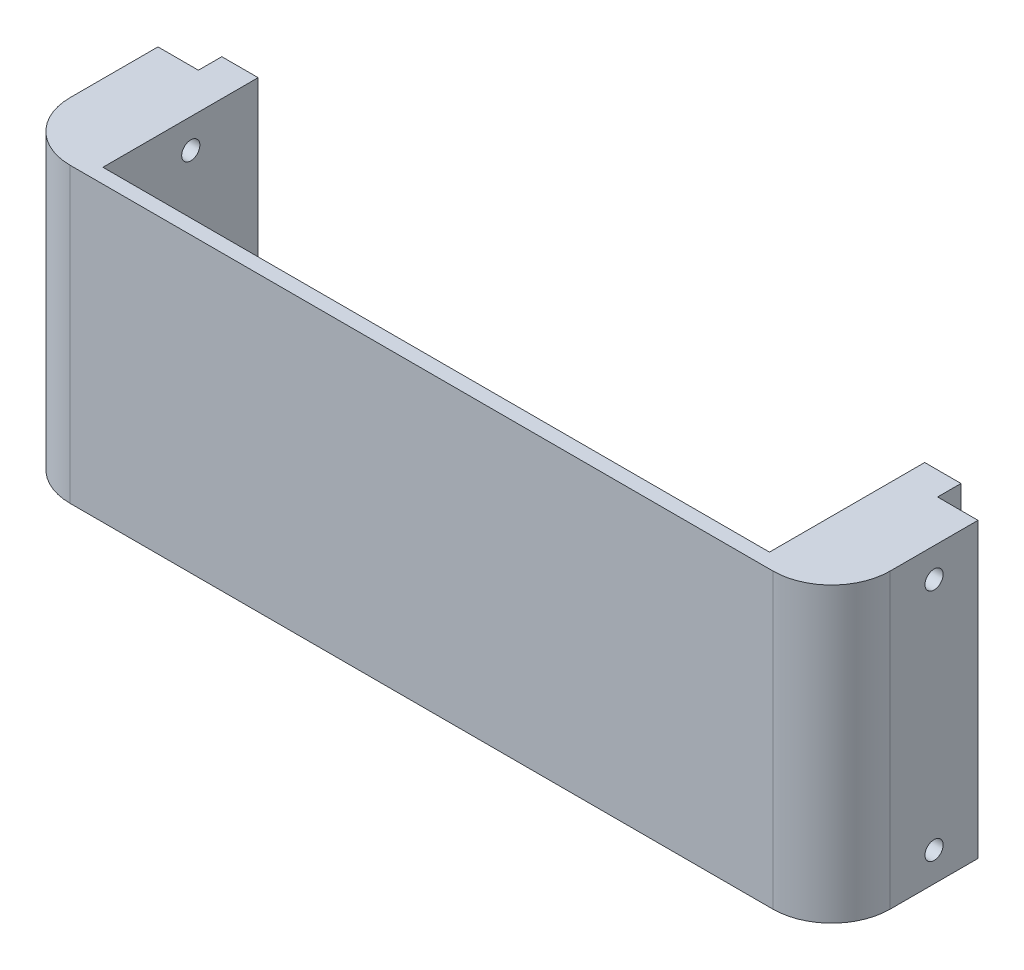
SolidWorks part; units mm, degrees
ref_plane "Front Plane" through (0, 0, 0) normal (0, 0, 1) x (1, 0, 0)
ref_plane "Top Plane" through (0, 0, 0) normal (0, 1, 0) x (1, 0, 0)
ref_plane "Right Plane" through (0, 0, 0) normal (1, 0, 0) x (0, 0, -1)
other "Configuration Table"
sketch "草图1" plane through (0, 0, 0) normal (0, 0, 1) x (1, 0, 0)
  line L0 (-15, 22) -> (-15, -22)
  line L1 (0, 22) -> (15, 22)
  line L2 (0, 22) -> (-15, 22)
  line L3 (15, 22) -> (15, -22)
  line L4 (15, -22) -> (-15, -22)
extrude "凸台-拉伸1" add sketch "草图1" along normal blind 14 contours L0 L4 L3 L1 L2
sketch "草图2" plane through (0, 22, 0) normal (0, 1, 0) x (1, 0, 0)
  line L3 (10, -4) -> (15, -14)
  line L4 (15, -14) -> (-15, -14)
  line L6 (-15, -14) -> (-10, -4)
  line L8 (3.1, -4) -> (3.1, 0)
  line L9 (-15, 0) -> (15, 0) construction
  line L10 (3.1, 0) -> (15, 0)
  line L11 (15, 0) -> (15, -14)
  line L12 (10, -4) -> (3.1, -4)
  line L13 (-3.1, -4) -> (-10, -4)
  line L14 (-15, -14) -> (-15, 0)
  line L15 (-15, 0) -> (-3.1, 0)
  line L16 (-3.1, 0) -> (-3.1, -4)
  line M14 (15, 0) -> (-15, 0)
  line M15 (-15, 0) -> (-15, -14)
  line M17 (15, -14) -> (15, 0)
extrude "切除-拉伸1" cut sketch "草图2" against normal blind 44 contours L16 L6 L13 M14 M15 | L12 L3 L8 M17 M14
sketch "草图3" plane through (0, 0, 0) normal (0, 0, -1) x (-1, 0, 0)
  line L2 (-3.1, 3.1) -> (-3.1, -3.1)
  line L4 (3.1, -22) -> (3.1, 22) construction
  line L5 (3.1, 3.1) -> (-3.1, 3.1)
  line L6 (-3.1, -22) -> (-3.1, 22) construction
  line L9 (-3.1, -3.1) -> (3.1, -3.1)
  line L10 (3.1, -22) -> (3.1, 22) construction
  line L11 (3.1, -3.1) -> (3.1, 3.1)
extrude "切除-拉伸2" cut sketch "草图3" against normal blind 4 contours L2 L9 L11 L5
sketch "草图4" plane through (0, 0, 14) normal (0, 0, 1) x (1, 0, 0)
  circle A0 centre (0, 0) radius 4
extrude "切除-拉伸3" cut sketch "草图4" against normal blind 5
sketch "草图5" plane through (0, 0, 9) normal (0, 0, 1) x (1, 0, 0)
  circle A0 centre (0, 0) radius 2.6
extrude "切除-拉伸4" cut sketch "草图5" against normal blind 5 contours A0
sketch "草图6" plane through (0, 0, 14) normal (0, 0, 1) x (1, 0, 0)
  circle A0 centre (0, 0) radius 4
extrude "凸台-拉伸2" add sketch "草图6" against normal blind 10
sketch "草图7" plane through (0, -22, 0) normal (0, -1, 0) x (-1, 0, 0)
  line L0 (-10, -4) -> (-3.1, -4) construction
  line L1 (3.1, 0) -> (-3.1, 0)
  line L2 (3.1, 0) -> (3.1, -4)
  line L3 (3.1, -4) -> (-3.1, -4)
  line L4 (-3.1, 0) -> (-3.1, -4)
  line L5 (-3.1, -4) -> (-3.1, 0) construction
extrude "凸台-拉伸3" add sketch "草图7" against normal blind 40
sketch "草图8" plane through (0, -22, 0) normal (0, -1, 0) x (1, 0, 0)
  line L0 (-10, 4) -> (-10, 14)
  line L1 (15, 14) -> (-15, 14) construction
  line L2 (-10, 14) -> (-15, 14)
  line L3 (-15, 14) -> (-10, 4)
  line L4 (10, 4) -> (10, 14)
  line L5 (10, 14) -> (15, 14)
  line L6 (15, 14) -> (10, 4)
  line M9 (10, 4) -> (15, 14)
  line M10 (15, 14) -> (-15, 14)
  line M11 (-15, 14) -> (-10, 4)
extrude "切除-拉伸5" cut sketch "草图8" against normal blind 50 contours L0 M11 M10 | L4 M9 M10
sketch "草图9" plane through (0, -22, 0) normal (0, -1, 0) x (1, 0, 0)
  line L0 (-10, 4) -> (-10, 29)
  line L5 (10, 4) -> (-10, 4)
  line L6 (10, 4) -> (10, 29)
  line L7 (-10, 29) -> (10, 29)
extrude "凸台-拉伸4" add sketch "草图9" against normal blind 44 contours L7 L6 L5 L0
sketch "草图10" plane through (0, -22, 0) normal (0, -1, 0) x (1, 0, 0)
  line L0 (-10, 29) -> (-10, 19)
  line L1 (-10, 4) -> (-10, 29) construction
  line L2 (0, 29) -> (-10, 29)
  arc A0 (-10, 19) -> (0, 29) centre (0, 19) cw
extrude "切除-拉伸6" cut sketch "草图10" against normal blind 44
sketch "草图11" plane through (0, -22, 0) normal (0, -1, 0) x (1, 0, 0)
  line L1 (120, 0) -> (123.1, 0)
  line L2 (116.9, 4) -> (110, 4)
  line L3 (123.1, 0) -> (123.1, 4)
  line L4 (123.1, 4) -> (130, 4)
  line L9 (116.9, 4) -> (116.9, 0)
  line L10 (116.9, 0) -> (120, 0)
  line L11 (10, 29) -> (110, 29)
  line L12 (10, 29) -> (10, 26.5)
  line L13 (10, 4) -> (10, 29) construction
  line L14 (10, 26.5) -> (110, 26.5)
  line L15 (110, 26.5) -> (110, 4)
  line L17 (110, 29) -> (120, 29)
  line L18 (130, 19) -> (130, 4)
  arc A0 (130, 19) -> (120, 29) centre (120, 19) ccw
extrude "凸台-拉伸5" add sketch "草图11" against normal blind 44 contours L17 A0 L18 L4 L3 L1 L10 L9 L2 L15 L14 L12 L11
sketch "草图12" plane through (0, 22, 0) normal (0, 1, 0) x (1, 0, 0)
  line L0 (3.1, -4) -> (10, -4)
  line L1 (10, -4) -> (10, -26.5)
  line L2 (10, -26.5) -> (3.1, -26.5)
  line L3 (3.1, -26.5) -> (3.1, -4)
  line L4 (116.9, -4) -> (110, -4)
  line L5 (110, -4) -> (110, -26.5)
  line L6 (110, -26.5) -> (116.9, -26.5)
  line L7 (116.9, -26.5) -> (116.9, -4)
extrude "切除-拉伸7" cut sketch "草图12" against normal blind 50 contours L3 L0 L1 L2 | L7 L4 L5 L6
sketch "草图14" plane through (0, -22, 0) normal (0, -1, 0) x (-1, 0, 0)
  line L0 (3.1, 0) -> (3.1, -4)
  line L1 (3.1, -4) -> (10, -4)
  line L2 (10, -4) -> (10, -19)
  line L5 (0, -29) -> (-120, -29)
  line L8 (-130, -19) -> (-130, -4)
  line L9 (-130, -4) -> (-123.1, -4)
  line L10 (-123.1, -4) -> (-123.1, 0)
  line L11 (-123.1, 0) -> (-116.9, 0)
  line L12 (-116.9, 0) -> (-116.9, -26.5)
  line L13 (-116.9, -26.5) -> (-3.1, -26.5)
  line L14 (-3.1, -26.5) -> (-3.1, 0)
  line L15 (-3.1, 0) -> (3.1, 0)
  arc A0 (10, -19) -> (0, -29) centre (0, -19) cw
  arc A1 (-130, -19) -> (-120, -29) centre (-120, -19) ccw
  arc A2 (-130, -19) -> (-120, -29) centre (-120, -19) ccw construction
extrude "凸台-拉伸6" add sketch "草图14" along normal blind 6 contours L5 A1 L8 L9 L10 L11 L12 L13 L14 L15 L0 L1 L2 A0
sketch "草图15" plane through (-10, 0, 0) normal (-1, 0, 0) x (0, 0, 1)
  line L0 (4, 22) -> (19, -28)
  line L1 (19, -28) -> (29, -28) construction
  line L2 (19, 22) -> (19, -28) construction
  line L3 (11.5, -3) -> (11.5, 12)
  line L4 (11.5, -3) -> (11.5, -18)
  line L5 (11.5, 12) -> (19, 12)
  line L6 (11.5, -18) -> (19, -18)
  line L7 (11.5, 12) -> (11.5, 22)
  line L8 (11.5, -18) -> (11.5, -23)
  circle A0 centre (11.5, 17) radius 1.55
  circle A1 centre (11.5, -23) radius 1.55
extrude "切除-拉伸8" cut sketch "草图15" against normal blind 2000
